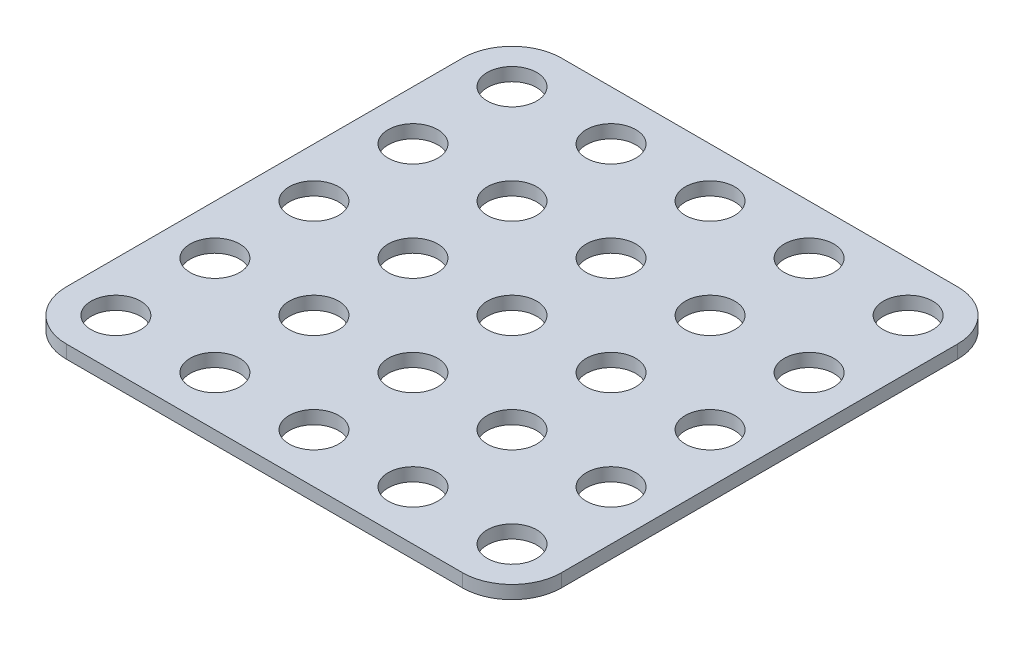
SolidWorks part; units mm, degrees
ref_plane "Front Plane" through (0, 0, 0) normal (0, 0, 1) x (1, 0, 0)
ref_plane "Top Plane" through (0, 0, 0) normal (0, 1, 0) x (1, 0, 0)
ref_plane "Right Plane" through (0, 0, 0) normal (1, 0, 0) x (0, 0, -1)
sketch "Sketch1" plane through (0, 0, 0) normal (0, 1, 0) x (1, 0, 0)
  line L0 (0, 75) -> (0, -75) construction
  line L1 (-75, -75) -> (75, -75)
  line L2 (-75, -75) -> (-75, 75)
  line L3 (-75, 75) -> (75, 75)
  line L4 (75, -75) -> (75, 75)
  line L5 (-75, -75) -> (75, 75) construction
  line L6 (-75, 75) -> (75, -75) construction
  line L7 (-75, 0) -> (75, 0) construction
  line L8 (-75, -60) -> (-60, -60) construction
  line L9 (-60, -60) -> (-60, -75) construction
  circle A1 centre (-60, -60) radius 7.5
  arc A2 (-75, -60) -> (-60, -75) centre (-60, -60) ccw
  arc A3 (75, -60) -> (60, -75) centre (60, -60) cw
  arc A4 (-75, 60) -> (-60, 75) centre (-60, 60) cw
  arc A5 (75, 60) -> (60, 75) centre (60, 60) ccw
  circle A6 centre (-30, -60) radius 7.5
  circle A7 centre (0, -60) radius 7.5
  circle A8 centre (30, -60) radius 7.5
  circle A9 centre (60, -60) radius 7.5
  circle A10 centre (-30, -30) radius 7.5
  circle A11 centre (0, -30) radius 7.5
  circle A12 centre (30, -30) radius 7.5
  circle A13 centre (60, -30) radius 7.5
  circle A14 centre (-30, 0) radius 7.5
  circle A15 centre (0, 0) radius 7.5
  circle A16 centre (30, 0) radius 7.5
  circle A17 centre (60, 0) radius 7.5
  circle A18 centre (-30, 30) radius 7.5
  circle A19 centre (0, 30) radius 7.5
  circle A20 centre (30, 30) radius 7.5
  circle A21 centre (60, 30) radius 7.5
  circle A22 centre (-30, 60) radius 7.5
  circle A23 centre (0, 60) radius 7.5
  circle A24 centre (30, 60) radius 7.5
  circle A25 centre (60, 60) radius 7.5
  circle A26 centre (-60, -30) radius 7.5
  circle A27 centre (-60, 0) radius 7.5
  circle A28 centre (-60, 30) radius 7.5
  circle A29 centre (-60, 60) radius 7.5
  point P0 (0, 0)
  dimension "D5" = 5
  dimension "D6" = 15
  dimension "D7" = 15
  dimension "D4" = 15
  dimension "D1" = 150
  dimension "D2" = 150
  dimension "D3" = 15
  dimension "D8" = 5
extrude "Boss-Extrude1" add sketch "Sketch1" along normal blind 4 contours L4 A5 L3 A4 L2 A2 L1 A3 A29 A28 A27 A26 A25 A24 A23 A22 A21 A20 A19 A18 A17 A16 A15 A14 A13 A12 A11 A10 A9
